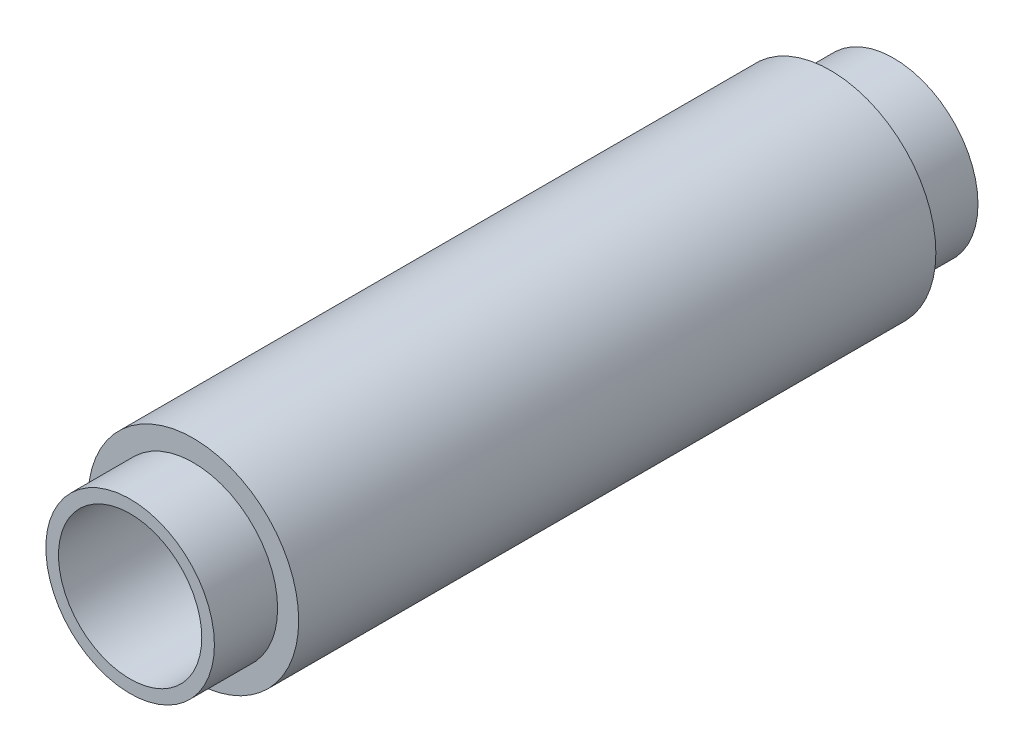
SolidWorks part; units mm, degrees
material "СТ3КП"
ref_plane "Спереди" through (0, 0, 0) normal (0, 0, 1) x (1, 0, 0)
ref_plane "Сверху" through (0, 0, 0) normal (0, 1, 0) x (1, 0, 0)
ref_plane "Справа" through (0, 0, 0) normal (1, 0, 0) x (0, 0, -1)
sketch "Эскиз1" plane through (0, 0, 0) normal (0, 1, 0) x (1, 0, 0)
  line L0 (-1000, 0) -> (49000, 0) construction
  line L1 (0, -1000) -> (0, 49000) construction
  line L3 (-25, 0) -> (-17, 0)
  line L4 (-25, 0) -> (-25, -75.6)
  line L5 (-20, -90.6) -> (-17, -90.6)
  line L6 (-17, 0) -> (-17, -90.6)
  line L7 (-21.5, -90.6) -> (21.5, -90.6) construction
  line L8 (21.5, -75.6) -> (-21.5, -75.6) construction
  line L9 (-20, -75.6) -> (-25, -75.6)
  line L10 (-20, -75.6) -> (-20, -90.6)
  line L13 (-20, -77.1) -> (-20, -89.1) construction
  dimension "D1" = 34
  dimension "D2" = 50
revolve "Повернуть1" add sketch "Эскиз1" angle 360 about L1
mirror "Зеркальное отражение1" about plane through (-25, 0, 0) normal (0, 0, 1) of "Повернуть1"
